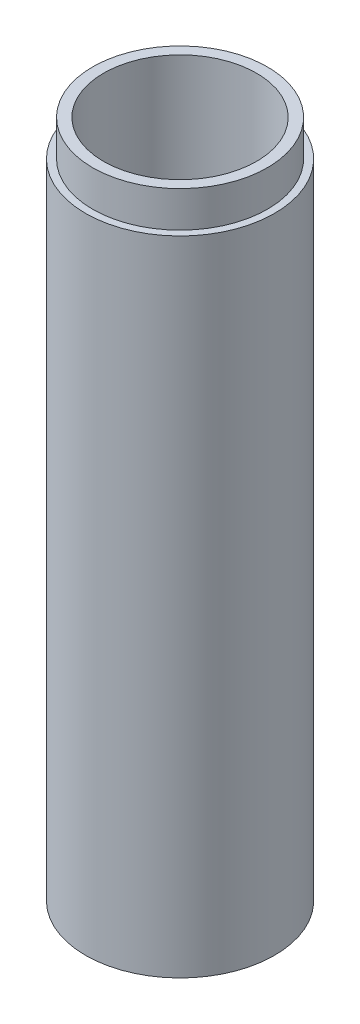
SolidWorks part; units mm, degrees
material "Brass"
ref_plane "Front Plane" through (0, 0, 0) normal (0, 0, 1) x (1, 0, 0)
ref_plane "Top Plane" through (0, 0, 0) normal (0, 1, 0) x (1, 0, 0)
ref_plane "Right Plane" through (0, 0, 0) normal (1, 0, 0) x (0, 0, -1)
sketch "Sketch2" plane through (0, 0, 0) normal (0, 0, 1) x (1, 0, 0)
  line L0 (11.5581, 85) -> (11.5581, 89.7625)
  line L1 (10.1188, 0) -> (12.5, 0)
  line L3 (11.5581, 85) -> (12.5, 85)
  line L4 (12.5, 0) -> (12.5, 85)
  line L5 (11.5581, 89.7625) -> (10.1187, 89.7625)
  line L6 (0, 96.7892) -> (0, 0) construction
  line L7 (10.1187, 89.7625) -> (10.1188, 2.3812)
  line L11 (0, 2.3812) -> (0, 0)
  line L12 (10.1188, 0) -> (0, 0) construction
  line L13 (0, 2.3812) -> (10.1188, 2.3812)
  line L14 (0, 0) -> (10.1188, 0)
  line L15 (10.1188, 2.3812) -> (10.1188, 0) construction
  dimension "D1" = 85
  dimension "D2" = 12.5
  dimension "D3" = 2.3813
  dimension "D4" = 4.7625
revolve "Revolve2" add sketch "Sketch2" angle 360 about L6
